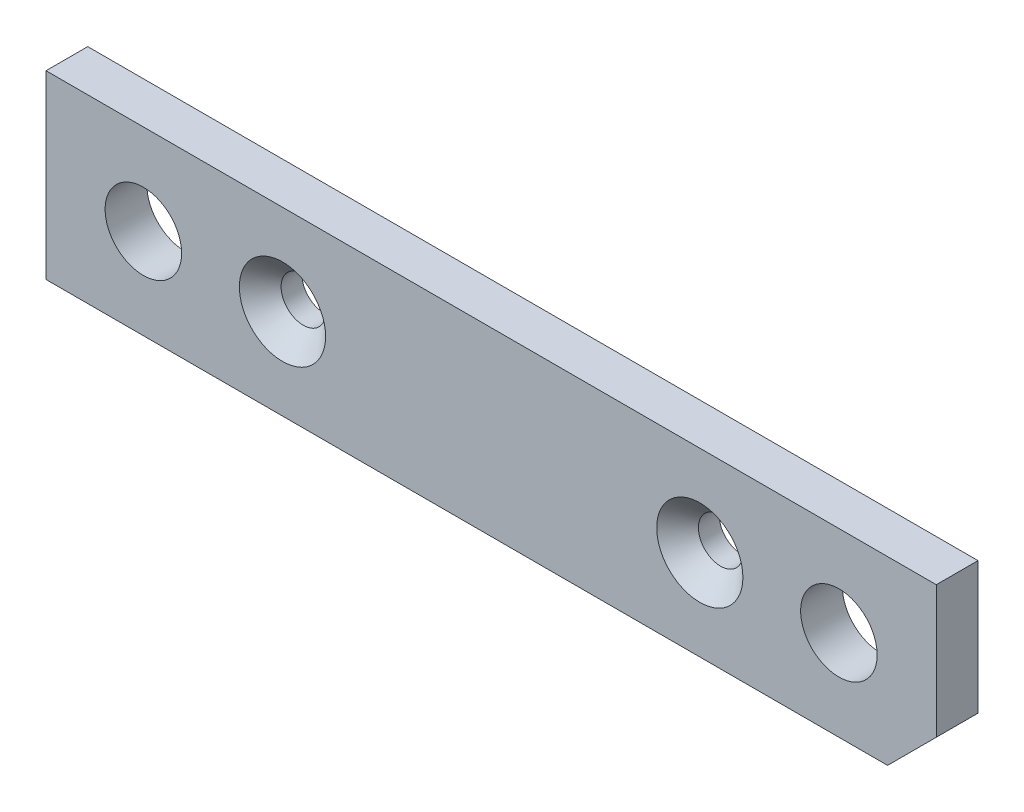
SolidWorks part; units mm, degrees
ref_plane "前视基准面" through (0, 0, 0) normal (0, 0, 1) x (1, 0, 0)
ref_plane "上视基准面" through (0, 0, 0) normal (0, 1, 0) x (1, 0, 0)
ref_plane "右视基准面" through (0, 0, 0) normal (1, 0, 0) x (0, 0, -1)
sketch "草图1" plane through (0, 0, 0) normal (0, 0, 1) x (1, 0, 0)
  line L0 (25, 0) -> (-25, 0) construction
  line L1 (0, 6.5) -> (0, -6.5) construction
  line L2 (32, -6.5) -> (-32, -6.5)
  line L3 (32, -6.5) -> (32, 6.5)
  line L4 (32, 6.5) -> (-32, 6.5)
  line L5 (-32, -6.5) -> (-32, 6.5)
  line L6 (32, -6.5) -> (-32, 6.5) construction
  line L7 (32, 6.5) -> (-32, -6.5) construction
  circle A0 centre (-25, 0) radius 2.75
  circle A1 centre (25, 0) radius 2.75
  circle A2 centre (-15, 0) radius 1.6
  circle A3 centre (15, 0) radius 1.6
  point P4 (0, 0)
  point P7 (0, 0)
  dimension "D1" = 13
  dimension "D4" = 5.5
  dimension "D5" = 30
  dimension "D6" = 3.2
  dimension "D2" = 64
  dimension "D3" = 50
extrude "凸台-拉伸1" add sketch "草图1" along normal mid plane 3
chamfer "倒角1" distance 3.5 angle 45 1 edges at (32, -6.5, 0)
chamfer "倒角2" distance 1.5 angle 45 2 edges at (13.4, 0, 1.5) (-13.4, 0, 1.5)
